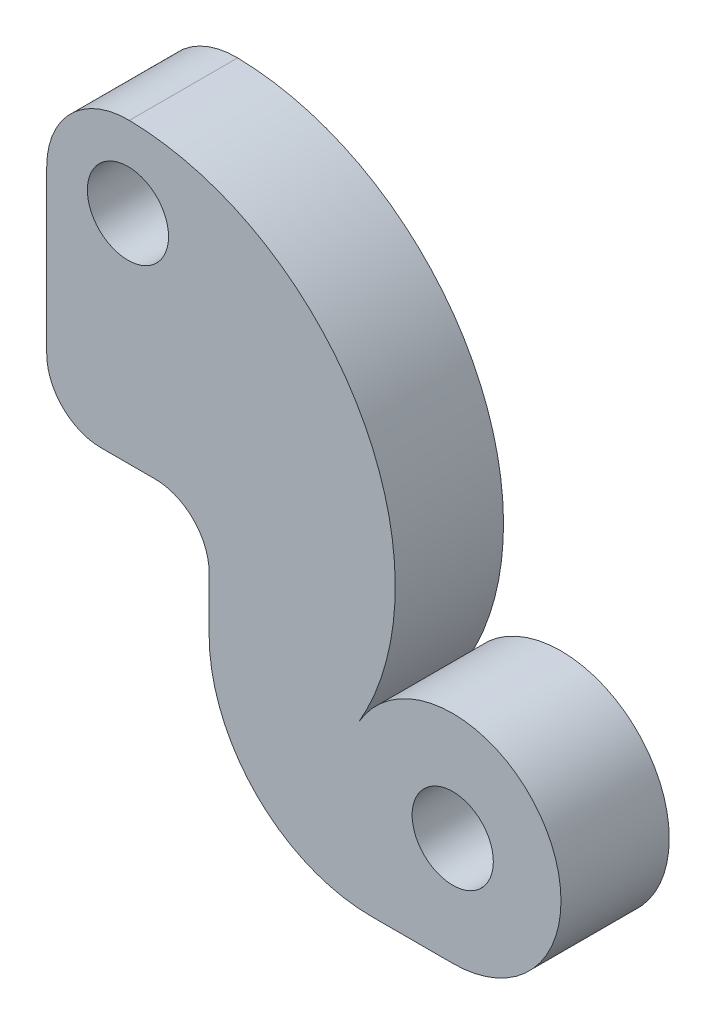
SolidWorks part; units mm, degrees
ref_plane "Front Plane" through (0, 0, 0) normal (0, 0, 1) x (1, 0, 0)
ref_plane "Top Plane" through (0, 0, 0) normal (0, 1, 0) x (1, 0, 0)
ref_plane "Right Plane" through (0, 0, 0) normal (1, 0, 0) x (0, 0, -1)
sketch "Sketch1" plane through (0, 0, 0) normal (0, 0, 1) x (1, 0, 0)
  line L0 (0, 0) -> (0, 29850.5851) construction
  line L1 (0, 0) -> (29850.5851, 0) construction
  line L2 (-75, 70) -> (-75, 40)
  line L3 (-65, 30) -> (-55, 30)
  line L4 (-45, 20) -> (-45, 10)
  line L5 (-15, -20) -> (0, -20)
  circle A2 centre (0, 0) radius 7.5
  arc A3 (0, -20) -> (-17.3196, 10.0016) centre (0, 0) ccw
  circle A4 centre (-60, 70) radius 7.5
  arc A5 (-59.7349, 84.9977) -> (-75, 70) centre (-60, 70) ccw
  arc A6 (-59.7349, 84.9977) -> (-17.3196, 10.0016) centre (-60.6186, 35.0055) cw
  arc A7 (-75, 40) -> (-65, 30) centre (-65, 40) ccw
  arc A8 (-55, 30) -> (-45, 20) centre (-55, 20) cw
  arc A9 (-45, 10) -> (-15, -20) centre (-15, 10) ccw
  dimension "D1" = 15
  dimension "D2" = 40
  dimension "D4" = 60
  dimension "D3" = 15
  dimension "D6" = 30
  dimension "D7" = 50
  dimension "D8" = 45
  dimension "D9" = 40
  dimension "D10" = 10
  dimension "D12" = 30
  dimension "D11" = 10
  dimension "D5" = 70
extrude "Boss-Extrude1" add sketch "Sketch1" along normal mid plane 20
